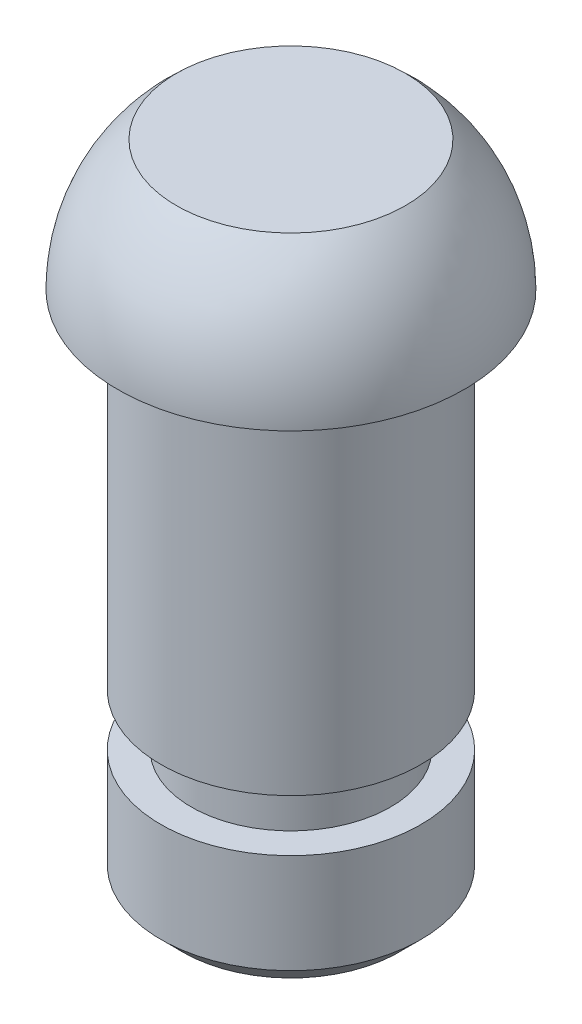
SolidWorks part; units mm, degrees
ref_plane "Front Plane" through (0, 0, 0) normal (0, 0, 1) x (1, 0, 0)
ref_plane "Top Plane" through (0, 0, 0) normal (0, 1, 0) x (1, 0, 0)
ref_plane "Right Plane" through (0, 0, 0) normal (1, 0, 0) x (0, 0, -1)
sketch "Sketch4" plane through (0, 0, 0) normal (0, 0, 1) x (1, 0, 0)
  line L0 (0, 0) -> (0, 6)
  line L2 (1.5, 6) -> (1.5, 2)
  line L3 (1.5, 2) -> (1.15, 2)
  line L4 (1.15, 2) -> (1.15, 1.4)
  line L5 (1.15, 1.4) -> (1.5, 1.4)
  line L6 (1.5, 1.4) -> (1.5, 0)
  line L7 (1.5, 0) -> (0, 0)
  line L8 (1.5, 6) -> (2, 6)
  line L9 (0, 7.5) -> (1.3229, 7.5)
  line L10 (0, 6) -> (0, 7.5)
  arc A0 (2, 6) -> (1.3229, 7.5) centre (0, 6) ccw
  dimension "D7" = 4
  dimension "D1" = 6
  dimension "D2" = 1.5
  dimension "D3" = 1.5
  dimension "D4" = 1.15
  dimension "D5" = 4
  dimension "D6" = 1.4
revolve "Revolve11" add sketch "Sketch4" angle 360 about L0
chamfer "Chamfer1" distance 0.25 angle 45 1 edges at (0, 0, -1.5)
